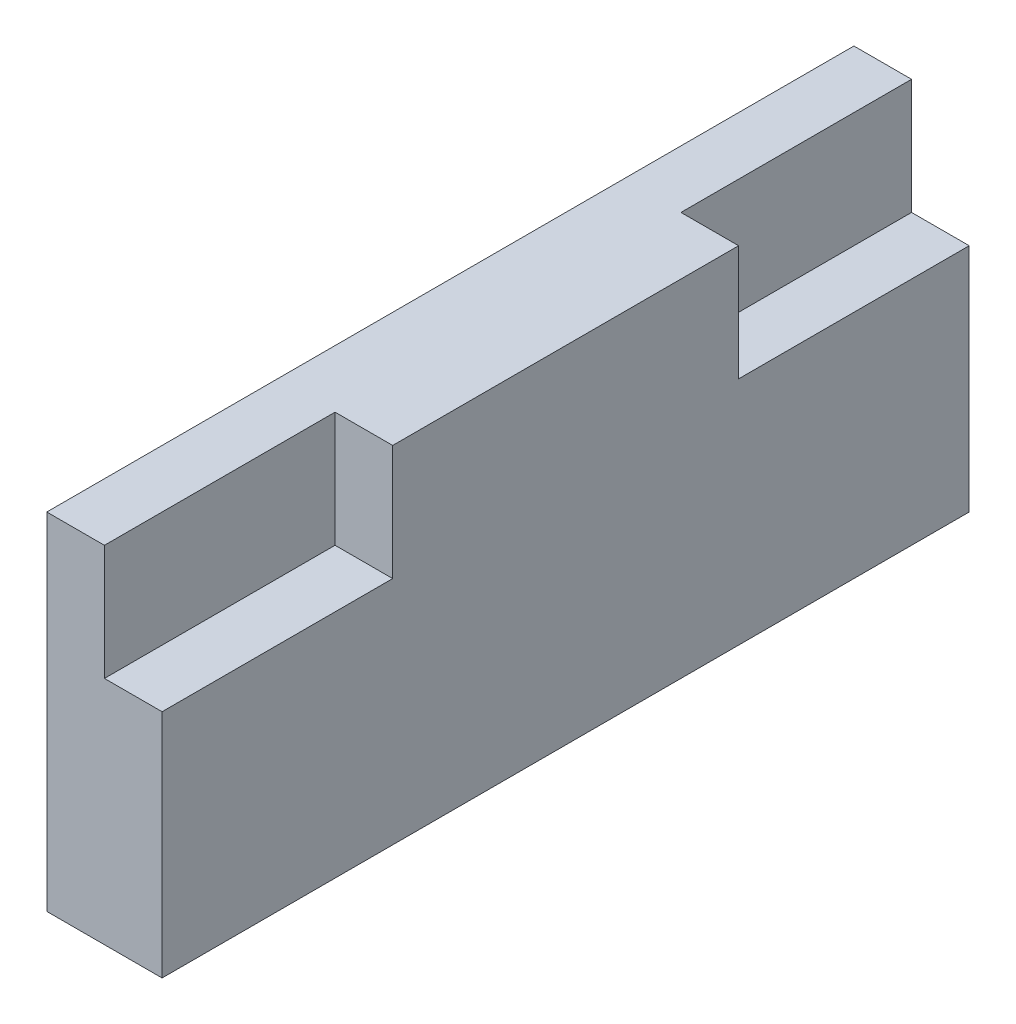
SolidWorks part; units mm, degrees
ref_plane "Front Plane" through (0, 0, 0) normal (0, 0, 1) x (1, 0, 0)
ref_plane "Top Plane" through (0, 0, 0) normal (0, 1, 0) x (1, 0, 0)
ref_plane "Right Plane" through (0, 0, 0) normal (1, 0, 0) x (0, 0, -1)
sketch "Sketch1" plane through (0, 0, 0) normal (0, 1, 0) x (1, 0, 0)
  line L1 (-138.0578, 116.2433) -> (-112.6578, 116.2433)
  line L2 (-138.0578, 116.2433) -> (-138.0578, -61.5567)
  line L3 (-138.0578, -61.5567) -> (-112.6578, -61.5567)
  line L4 (-112.6578, 116.2433) -> (-112.6578, -61.5567)
  dimension "D1" = 177.8
  dimension "D2" = 25.4
extrude "Boss-Extrude1" add sketch "Sketch1" along normal blind 76.2
sketch "Sketch2" plane through (-112.6578, 0, 0) normal (1, 0, 0) x (0, 0, -1)
  line L0 (116.2433, 50.8) -> (65.4433, 50.8)
  line L1 (-61.5567, 76.2) -> (-10.7567, 76.2)
  line L2 (-61.5567, 76.2) -> (-61.5567, 50.8)
  line L3 (-61.5567, 50.8) -> (-10.7567, 50.8)
  line L4 (-10.7567, 76.2) -> (-10.7567, 50.8)
  line L5 (-61.5567, 0) -> (116.2433, 0) construction
  line L6 (-61.5567, 76.2) -> (116.2433, 76.2) construction
  line L7 (27.3433, 76.2) -> (27.3433, 0) construction
  line L8 (65.4433, 76.2) -> (65.4433, 50.8)
  line L9 (116.2433, 76.2) -> (65.4433, 76.2)
  line L10 (116.2433, 76.2) -> (116.2433, 50.8)
  dimension "D1" = 25.4
  dimension "D2" = 50.8
extrude "Cut-Extrude1" cut sketch "Sketch2" against normal blind 12.7
